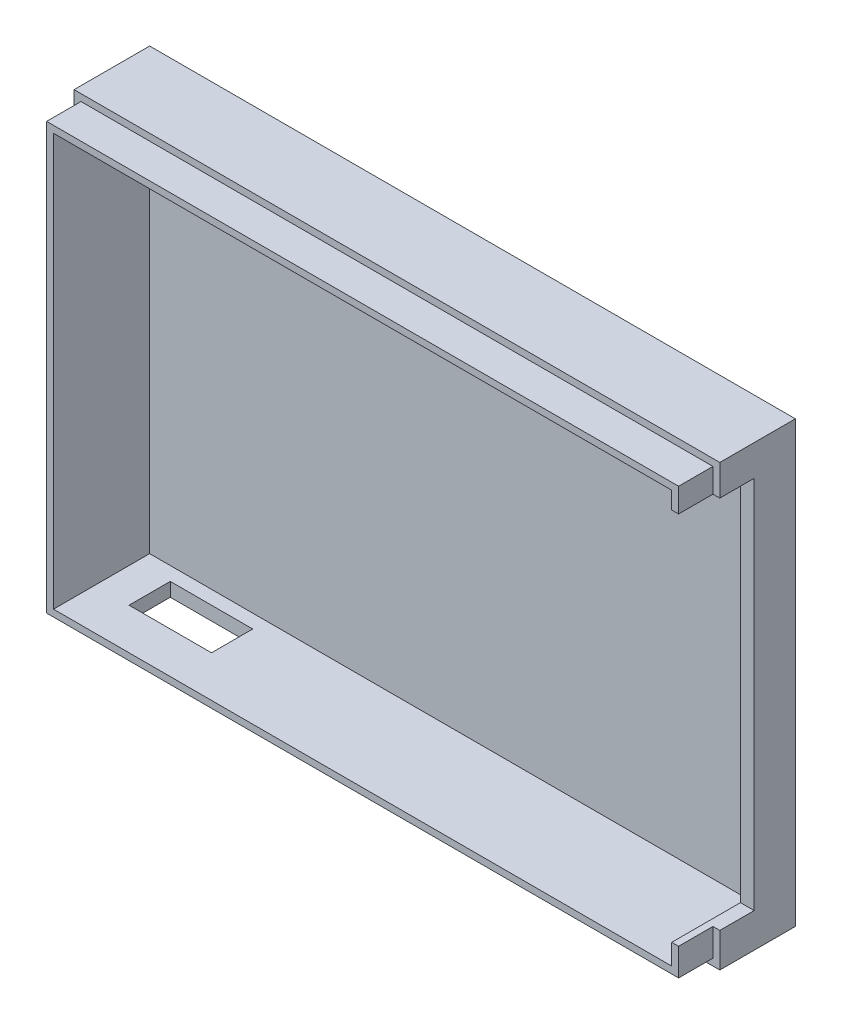
SolidWorks part; units mm, degrees
ref_plane "Front Plane" through (0, 0, 0) normal (0, 0, 1) x (1, 0, 0)
ref_plane "Top Plane" through (0, 0, 0) normal (0, 1, 0) x (1, 0, 0)
ref_plane "Right Plane" through (0, 0, 0) normal (1, 0, 0) x (0, 0, -1)
sketch "Sketch1" plane through (0, 0, 0) normal (0, 0, 1) x (1, 0, 0)
  line L0 (0, 46.1675) -> (0, -47.2288) construction
  line L1 (-66.8632, 0) -> (61.7689, 0) construction
  line L3 (-47, 32) -> (47, 32)
  line L4 (-47, 32) -> (-47, -32)
  line L5 (-47, -32) -> (47, -32)
  line L6 (47, 32) -> (47, -32)
  dimension "D1" = 94
  dimension "D2" = 47
  dimension "D3" = 64
  dimension "D4" = 32
extrude "Boss-Extrude1" add sketch "Sketch1" along normal blind 16
sketch "Sketch2" plane through (0, 0, 16) normal (0, 0, 1) x (1, 0, 0)
  line L0 (47, 32) -> (-47, 32) construction
  line L1 (-45, 30) -> (45, 30)
  line L2 (-45, 30) -> (-45, -30)
  line L3 (-45, -30) -> (45, -30)
  line L4 (45, 30) -> (45, -30)
  line L5 (-47, -32) -> (47, -32) construction
  line L6 (-47, 32) -> (-47, -32) construction
  line L7 (47, -32) -> (47, 32) construction
  dimension "D1" = 2
  dimension "D2" = 2
  dimension "D3" = 2
  dimension "D4" = 2
extrude "Cut-Extrude1" cut sketch "Sketch2" against normal blind 14
sketch "Sketch4" plane through (0, 0, 16) normal (0, 0, 1) x (1, 0, 0)
  line L1 (-47, 32) -> (47, 32)
  line L2 (-47, 32) -> (-47, -32)
  line L3 (-47, -32) -> (47, -32)
  line L4 (47, 32) -> (47, -32)
  line L5 (-46, 31) -> (46, 31)
  line L6 (-46, 31) -> (-46, -31)
  line L7 (-46, -31) -> (46, -31)
  line L8 (46, 31) -> (46, -31)
  dimension "D1" = 1
  dimension "D2" = 1
  dimension "D3" = 1
  dimension "D4" = 1
extrude "Cut-Extrude2" cut sketch "Sketch4" against normal blind 5
sketch "Sketch6" plane through (0, -32, 0) normal (0, -1, 0) x (1, 0, 0)
  line L0 (-47, 11) -> (-47, 0) construction
  line L1 (-40, 10) -> (-28, 10)
  line L2 (-40, 10) -> (-40, 4)
  line L3 (-40, 4) -> (-28, 4)
  line L4 (-28, 10) -> (-28, 4)
  line L5 (-47, 0) -> (47, 0) construction
  dimension "D1" = 6
  dimension "D2" = 12
  dimension "D3" = 7
  dimension "D4" = 4
extrude "Cut-Extrude3" cut sketch "Sketch6" against normal up to next
sketch "Sketch8" plane through (45, 0, 0) normal (-1, 0, 0) x (0, 0, 1)
  line L0 (16, 31) -> (16, -31) construction
  line L1 (16, 27.5) -> (6, 27.5)
  line L2 (16, 27.5) -> (16, -27)
  line L3 (16, -27) -> (6, -27)
  line L4 (6, 27.5) -> (6, -27)
  line L5 (2, 30) -> (16, 30) construction
  line L6 (2, -30) -> (16, -30) construction
  line L7 (2, -30) -> (2, 30) construction
  dimension "D1" = 2.5
  dimension "D2" = 3
  dimension "D3" = 4
extrude "Cut-Extrude4" cut sketch "Sketch8" against normal up to next
